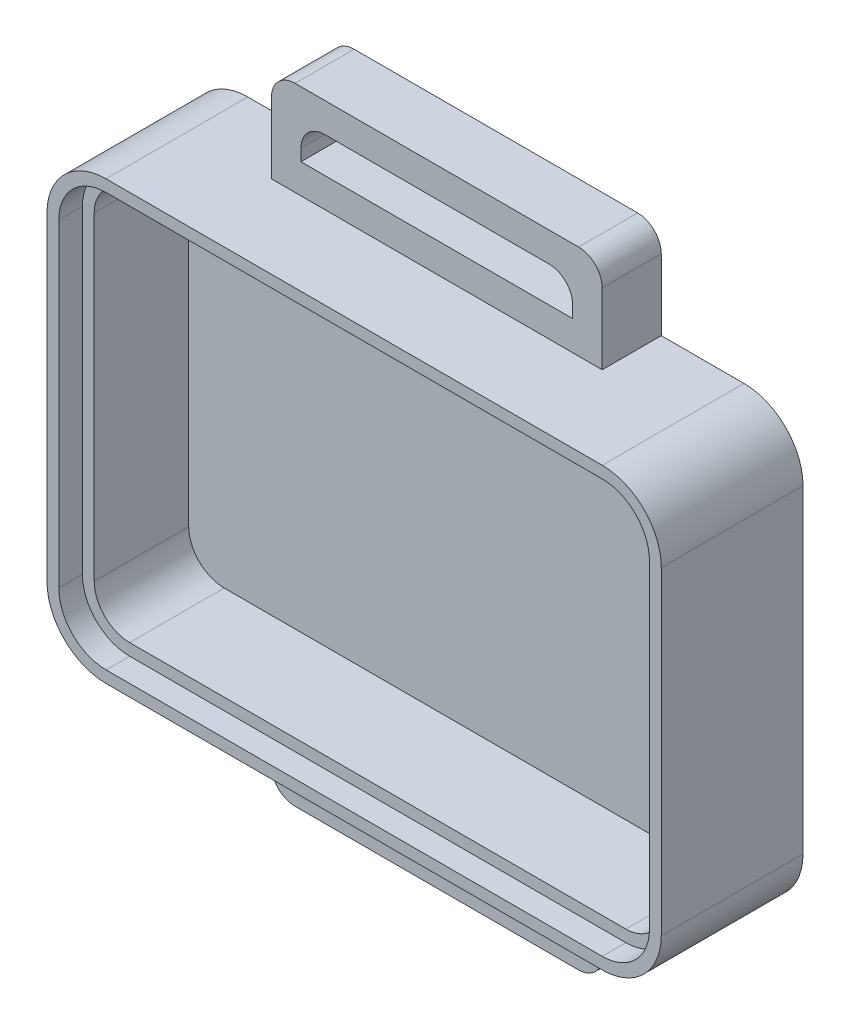
SolidWorks part; units mm, degrees
ref_plane "Plan de face" through (0, 0, 0) normal (0, 0, 1) x (1, 0, 0)
ref_plane "Plan de dessus" through (0, 0, 0) normal (0, 1, 0) x (1, 0, 0)
ref_plane "Plan de droite" through (0, 0, 0) normal (1, 0, 0) x (0, 0, -1)
sketch "Esquisse1" plane through (0, 0, 0) normal (0, 0, 1) x (1, 0, 0)
  line L1 (5, 0) -> (47, 0)
  line L2 (0, 5) -> (0, 32)
  line L3 (5, 37) -> (47, 37)
  line L4 (52, 5) -> (52, 32)
  arc A0 (47, 37) -> (52, 32) centre (47, 32) cw
  arc A1 (47, 0) -> (52, 5) centre (47, 5) ccw
  arc A2 (5, 0) -> (0, 5) centre (5, 5) cw
  arc A3 (0, 32) -> (5, 37) centre (5, 32) cw
  point P9 (52, 0)
  point P12 (0, 0)
  point P15 (0, 37)
  dimension "D3" = 5
  dimension "D1" = 37
  dimension "D2" = 52
extrude "Boss.-Extru.1" add sketch "Esquisse1" along normal blind 12
shell "Coque5" thickness 2
sketch "Esquisse3" plane through (0, 0, 12) normal (0, 0, 1) x (1, 0, 0)
  line L8 (47, 36) -> (5, 36)
  line L9 (1, 32) -> (1, 5)
  line L10 (5, 1) -> (47, 1)
  line L11 (51, 5) -> (51, 32)
  line L12 (47, 36) -> (5, 36)
  line L13 (1, 32) -> (1, 5)
  line L14 (5, 1) -> (47, 1)
  line L15 (51, 5) -> (51, 32)
  arc A8 (51, 32) -> (47, 36) centre (47, 32) ccw
  arc A9 (5, 36) -> (1, 32) centre (5, 32) ccw
  arc A10 (1, 5) -> (5, 1) centre (5, 5) ccw
  arc A11 (47, 1) -> (51, 5) centre (47, 5) ccw
  arc A12 (51, 32) -> (47, 36) centre (47, 32) ccw
  arc A13 (5, 36) -> (1, 32) centre (5, 32) ccw
  arc A14 (1, 5) -> (5, 1) centre (5, 5) ccw
  arc A15 (47, 1) -> (51, 5) centre (47, 5) ccw
  dimension "D1" = 1
extrude "Enlèv. mat.-Extru.1" cut sketch "Esquisse3" against normal blind 2 contours A12 L12 A13 L13 A14 L14 A15 L15
sketch "Esquisse4" [suppressed] plane through (0, 0, 2) normal (0, 0, 1) x (1, 0, 0)
  line L0 (29.8171, 28.7082) -> (29.8171, 6.2082)
  line L1 (28.8171, 27.7082) -> (3.8171, 27.7082)
  line L2 (28.8171, 27.7082) -> (28.8171, 7.2082)
  line L3 (28.8171, 7.2082) -> (3.8171, 7.2082)
  line L4 (3.8171, 27.7082) -> (3.8171, 7.2082)
  line L5 (29.8171, 6.2082) -> (2.8171, 6.2082)
  line L6 (2.8171, 28.7082) -> (2.8171, 6.2082)
  line L7 (29.8171, 28.7082) -> (2.8171, 28.7082)
  dimension "D1" = 25
  dimension "D2" = 20.5
  dimension "D3" = 1
extrude "Boss.-Extru.3" [suppressed] add sketch "Esquisse4" along normal blind 5
sketch "Esquisse7" [suppressed] plane through (52, 0, 0) normal (1, 0, 0) x (0, 0, -1)
  circle A0 centre (-6, 36.365) radius 1.4
  dimension "D1" = 2.8
extrude "Enlèv. mat.-Extru.2" [suppressed] cut sketch "Esquisse7" against normal through all
sketch "Esquisse8" [suppressed] plane through (52, 0, 0) normal (1, 0, 0) x (0, 0, -1)
  circle A0 centre (-6, 0.635) radius 1.4
  dimension "D1" = 2.8
extrude "Enlèv. mat.-Extru.3" [suppressed] cut sketch "Esquisse8" against normal through all
sketch "Esquisse9" plane through (0, 0, 0) normal (-1, 0, 0) x (0, 0, 1)
  line L4 (6.55, 22.7082) -> (3.55, 22.7082)
  line L5 (6.55, 22.7082) -> (6.55, 12.7082)
  line L6 (6.55, 12.7082) -> (3.55, 12.7082)
  line L7 (3.55, 22.7082) -> (3.55, 12.7082)
  dimension "D2" = 10
  dimension "D3" = 3
extrude "Enlèv. mat.-Extru.4" [suppressed] cut sketch "Esquisse9" against normal up to vertex and the other way through all
sketch "Esquisse10" plane through (0, 0, 0) normal (0, 0, -1) x (-1, 0, 0)
  line L0 (-47, 37) -> (-5, 37) construction
  line L1 (-40, 37) -> (-12, 37)
  line L2 (-40, 37) -> (-40, 43)
  line L3 (-38, 45) -> (-14, 45)
  line L4 (-12, 37) -> (-12, 43)
  line L5 (-37.5, 39.5) -> (-37.5, 40.5)
  line L6 (-35.5, 42.5) -> (-16.5, 42.5)
  line L7 (-14.5, 39.5) -> (-14.5, 40.5)
  line L8 (-37.5, 39.5) -> (-14.5, 39.5)
  line L9 (-5, 0) -> (-47, 0) construction
  line L10 (-40, 0) -> (-12, 0)
  line L11 (-40, 0) -> (-40, -6)
  line L12 (-38, -8) -> (-14, -8)
  line L13 (-12, 0) -> (-12, -6)
  line L14 (-37.5, -2.5) -> (-37.5, -3.5)
  line L15 (-35.5, -5.5) -> (-16.5, -5.5)
  line L16 (-14.5, -2.5) -> (-14.5, -3.5)
  line L17 (-37.5, -2.5) -> (-14.5, -2.5)
  line L18 (-40, 0) -> (-40, -8) construction
  line L19 (-40, -8) -> (-12, -8) construction
  line L20 (-37.5, -2.5) -> (-37.5, -5.5) construction
  line L21 (-37.5, -5.5) -> (-14.5, -5.5) construction
  line L22 (-14.5, -2.5) -> (-14.5, -5.5) construction
  line L23 (-12, 0) -> (-12, -8) construction
  line L24 (-37.5, 39.5) -> (-37.5, 42.5) construction
  line L25 (-37.5, 42.5) -> (-14.5, 42.5) construction
  line L26 (-14.5, 39.5) -> (-14.5, 42.5) construction
  line L27 (-40, 45) -> (-12, 45) construction
  line L28 (-12, 37) -> (-12, 45) construction
  line L29 (-40, 37) -> (-40, 45) construction
  arc A0 (-40, -6) -> (-38, -8) centre (-38, -6) ccw
  arc A1 (-37.5, -3.5) -> (-35.5, -5.5) centre (-35.5, -3.5) ccw
  arc A2 (-16.5, -5.5) -> (-14.5, -3.5) centre (-16.5, -3.5) ccw
  arc A3 (-14, -8) -> (-12, -6) centre (-14, -6) ccw
  arc A4 (-37.5, 40.5) -> (-35.5, 42.5) centre (-35.5, 40.5) cw
  arc A5 (-16.5, 42.5) -> (-14.5, 40.5) centre (-16.5, 40.5) cw
  arc A6 (-14, 45) -> (-12, 43) centre (-14, 43) cw
  arc A7 (-40, 43) -> (-38, 45) centre (-38, 43) cw
  point P25 (-40, -8)
  point P44 (-12, 45)
  dimension "D7" = 2
  dimension "D2" = 12
  dimension "D5" = 8
  dimension "D4" = 2.5
  dimension "D6" = 2.5
extrude "Boss.-Extru.5" add sketch "Esquisse10" against normal blind 5
sketch "Esquisse12" plane through (52, 0, 0) normal (1, 0, 0) x (0, 0, -1)
  line L1 (-6.5976, 24.1838) -> (-4.5976, 24.1838)
  line L2 (-7.5976, 23.1838) -> (-7.5976, 15.3838)
  line L3 (-6.5976, 14.3838) -> (-4.5976, 14.3838)
  line L4 (-3.5976, 23.1838) -> (-3.5976, 15.3838)
  arc A0 (-4.5976, 14.3838) -> (-3.5976, 15.3838) centre (-4.5976, 15.3838) ccw
  arc A1 (-4.5976, 24.1838) -> (-3.5976, 23.1838) centre (-4.5976, 23.1838) cw
  arc A2 (-6.5976, 24.1838) -> (-7.5976, 23.1838) centre (-6.5976, 23.1838) ccw
  arc A3 (-7.5976, 15.3838) -> (-6.5976, 14.3838) centre (-6.5976, 15.3838) ccw
  point P9 (-3.5976, 24.1838)
  point P12 (-7.5976, 24.1838)
  point P15 (-7.5976, 14.3838)
  dimension "D3" = 1
  dimension "D1" = 9.8
  dimension "D2" = 4
